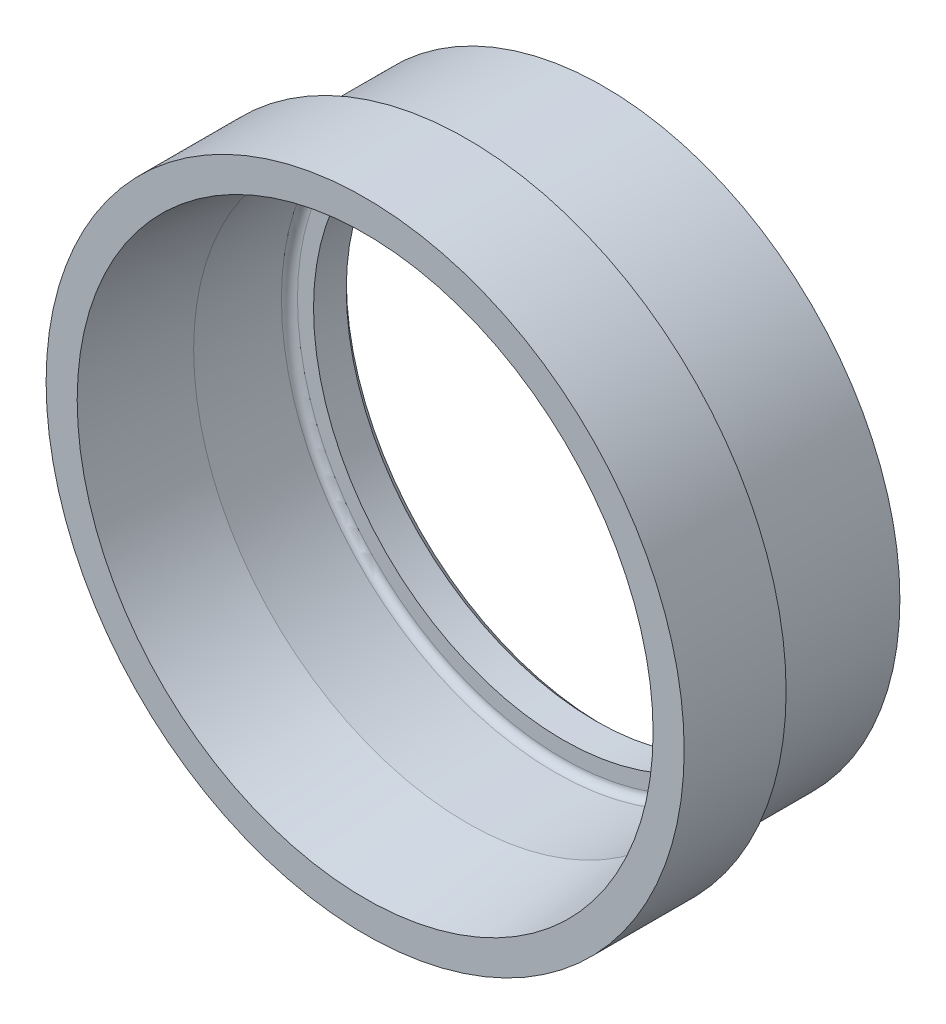
SolidWorks part; units mm, degrees
ref_plane "Front Plane" through (0, 0, 0) normal (0, 0, 1) x (1, 0, 0)
ref_plane "Top Plane" through (0, 0, 0) normal (0, 1, 0) x (1, 0, 0)
ref_plane "Right Plane" through (0, 0, 0) normal (1, 0, 0) x (0, 0, -1)
sketch "Sketch1" plane through (0, 0, 0) normal (0, 1, 0) x (1, 0, 0)
  line L0 (35.8775, 0) -> (39.751, 0)
  line L2 (39.751, 0) -> (39.751, 12.7)
  line L3 (39.751, 12.7) -> (36.9102, 12.7)
  line L4 (36.9102, 12.7) -> (36.9102, 29.718)
  line L5 (36.9102, 29.718) -> (31.0682, 29.718)
  line L6 (31.0682, 29.718) -> (31.0682, 24.638)
  line L7 (31.0682, 24.638) -> (34.0682, 24.638)
  line L8 (34.0682, 24.638) -> (34.0682, 12.7)
  line L9 (34.0682, 12.7) -> (35.8775, 0)
  line L10 (0, 0) -> (0, 31.6121)
revolve "Revolve1" add sketch "Sketch1" angle 360 about L10
fillet "Fillet1" radius 1 1 edges at (36.9102, 0, -12.7)
chamfer "Chamfer1" distance 1 angle 45 1 edges at (31.0682, 0, -29.718)
fillet "Fillet2" radius 1 1 edges at (34.0682, 0, -24.638)
